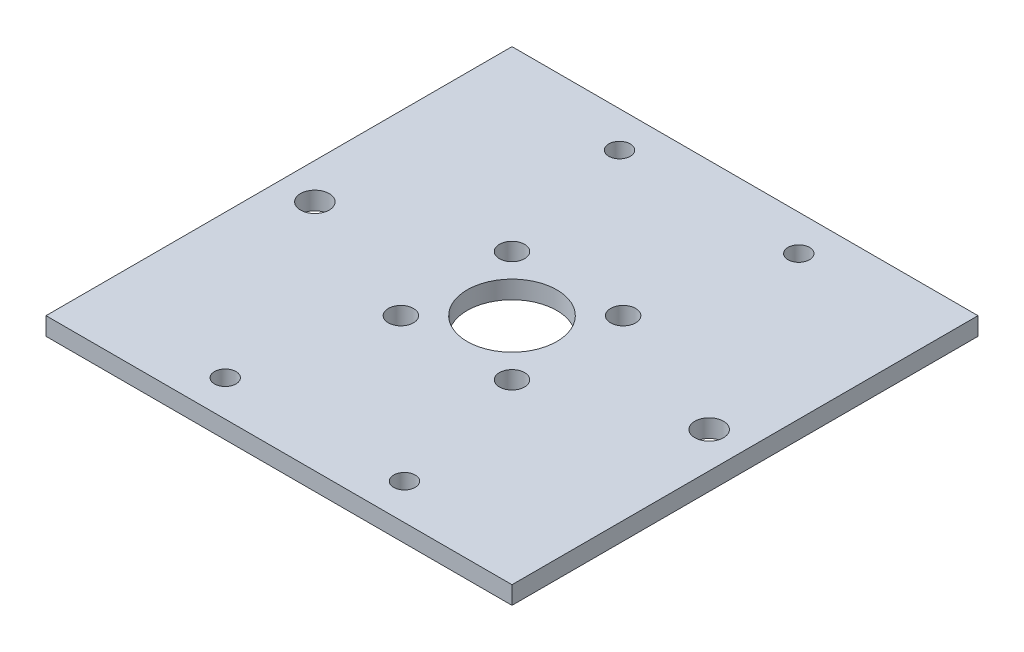
SolidWorks part; units mm, degrees
ref_plane "Front Plane" through (0, 0, 0) normal (0, 0, 1) x (1, 0, 0)
ref_plane "Top Plane" through (0, 0, 0) normal (0, 1, 0) x (1, 0, 0)
ref_plane "Right Plane" through (0, 0, 0) normal (1, 0, 0) x (0, 0, -1)
sketch "Sketch1" plane through (0, 0, 0) normal (0, 1, 0) x (1, 0, 0)
  line L0 (0, 65) -> (0, -65) construction
  line L1 (-65, 65) -> (65, 65)
  line L2 (-65, 65) -> (-65, -65)
  line L3 (-65, -65) -> (65, -65)
  line L4 (65, 65) -> (65, -65)
  line L5 (-65, 65) -> (65, -65) construction
  line L6 (-65, -65) -> (65, 65) construction
  circle A0 centre (-55, 0) radius 4
  circle A1 centre (55, 0) radius 4
  circle A2 centre (0, 0) radius 12.5
  point P0 (0, 0)
  dimension "D3" = 8
  dimension "D5" = 25
  dimension "D1" = 130
  dimension "D2" = 130
  dimension "D4" = 55
extrude "Boss-Extrude1" add sketch "Sketch1" along normal blind 5 contours L4 L1 L2 L3 A2 A0 A1
sketch "Sketch2" plane through (0, 5, 0) normal (0, 1, 0) x (1, 0, 0)
  line L2 (-65, 65) -> (65, 65) construction
  circle A0 centre (-25, 55) radius 3
  circle A1 centre (25, 55) radius 3
  circle A2 centre (25, -55) radius 3
  circle A3 centre (-25, -55) radius 3
  dimension "D1" = 6
  dimension "D2" = 10
  dimension "D3" = 50
extrude "Cut-Extrude1" cut sketch "Sketch2" against normal blind 10
sketch "Sketch3" plane through (0, 5, 0) normal (0, 1, 0) x (1, 0, 0)
  line L1 (-15.5, 15.5) -> (15.5, 15.5) construction
  line L2 (-15.5, 15.5) -> (-15.5, -15.5) construction
  line L3 (-15.5, -15.5) -> (15.5, -15.5) construction
  line L4 (15.5, 15.5) -> (15.5, -15.5) construction
  line L5 (-15.5, 15.5) -> (15.5, -15.5) construction
  line L6 (-15.5, -15.5) -> (15.5, 15.5) construction
  circle A0 centre (-15.5, 15.5) radius 3.5
  circle A1 centre (15.5, 15.5) radius 3.5
  circle A2 centre (-15.5, -15.5) radius 3.5
  circle A3 centre (15.5, -15.5) radius 3.5
  point P0 (0, 0)
  dimension "D3" = 7
  dimension "D1" = 31
  dimension "D2" = 31
extrude "Cut-Extrude2" cut sketch "Sketch3" against normal up to surface (5 mm away) up to face at (-25, 0, 58)
